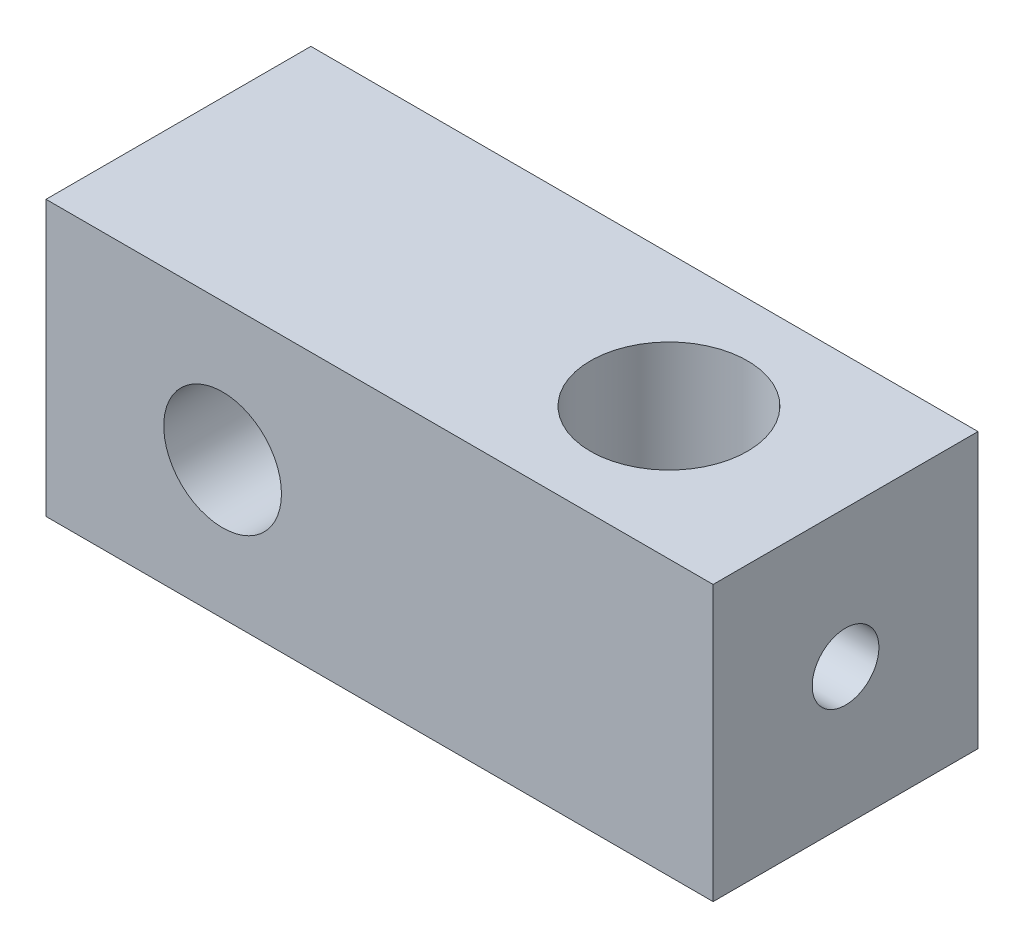
SolidWorks part; units mm, degrees
ref_plane "Front Plane" through (0, 0, 0) normal (0, 0, 1) x (1, 0, 0)
ref_plane "Top Plane" through (0, 0, 0) normal (0, 1, 0) x (1, 0, 0)
ref_plane "Right Plane" through (0, 0, 0) normal (1, 0, 0) x (0, 0, -1)
sketch "Sketch1" plane through (0, 0, 0) normal (0, 1, 0) x (1, 0, 0)
  line L1 (0, 0) -> (68, 0)
  line L2 (0, 0) -> (0, 27)
  line L3 (0, 27) -> (68, 27)
  line L4 (68, 0) -> (68, 27)
extrude "Boss-Extrude1" add sketch "Sketch1" along normal blind 28
sketch "Sketch2" plane through (0, 0, 0) normal (0, 0, 1) x (1, 0, 0)
  circle A1 centre (18, 14) radius 6
extrude "Cut-Extrude1" cut sketch "Sketch2" against normal blind 28
sketch "Sketch3" plane through (0, 28, 0) normal (0, 1, 0) x (1, 0, 0)
  circle A2 centre (50, 13.5) radius 8
extrude "Cut-Extrude2" cut sketch "Sketch3" against normal blind 28
hole_wizard "M8 Tapped Hole1" positions "Sketch4" profile "Sketch6" tap size "M8" standard "ISO"
sketch "Sketch4" plane through (68, 0, 0) normal (1, 0, 0) x (0, 0, -1)
  point P0 (13.5, 14)
sketch "Sketch6" plane through (68, 14, -13.5) normal (0, 1, 0) x (0, 0, -1)
  line L0 (0, 0) -> (0, 15)
  line L1 (0, 15) -> (3.4, 15)
  line L2 (3.4, 15) -> (3.4, 0)
  line L5 (3.4, 0) -> (0, 0)
  line L10 (0, 15) -> (-3.4, 15) construction
  line L11 (0, -6.35) -> (0, 107.95) construction
  dimension "Tap Drill Dia." = 6.8
  dimension "Tap Drill Depth" = 15
  dimension "Drill Angle" = 180
cosmetic thread "Hole Thread1" parameters "D1"=15, "D2"=8
